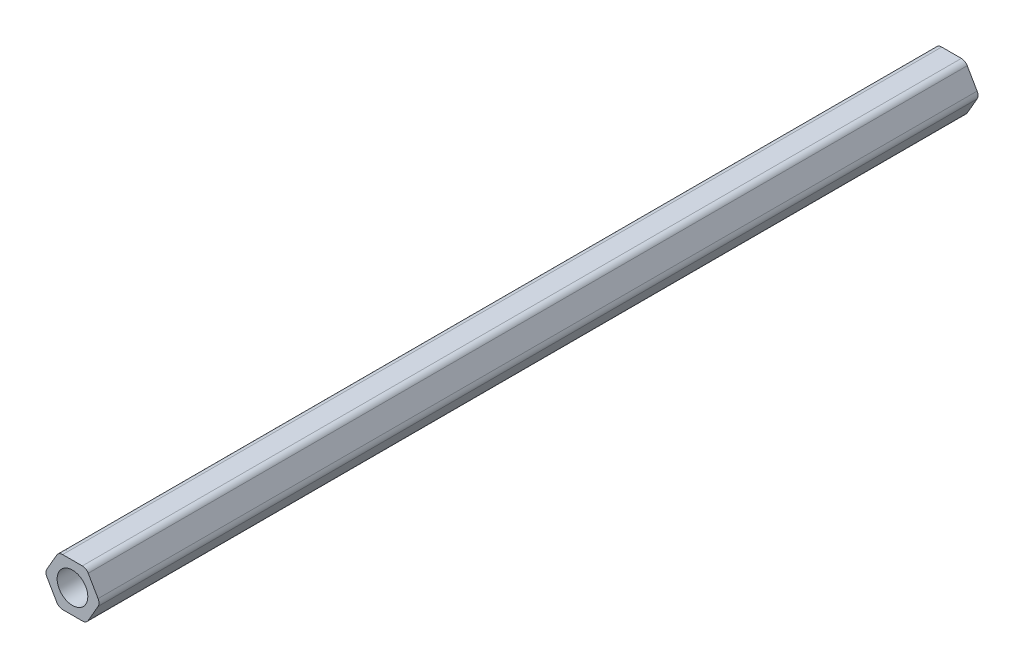
SolidWorks part; units mm, degrees
material "ABS"
ref_plane "Спереди" through (0, 0, 0) normal (0, 0, 1) x (1, 0, 0)
ref_plane "Сверху" through (0, 0, 0) normal (0, 1, 0) x (1, 0, 0)
ref_plane "Справа" through (0, 0, 0) normal (1, 0, 0) x (0, 0, -1)
sketch "Эскиз1" plane through (0, 0, 0) normal (0, 0, 1) x (1, 0, 0)
  line L1 (3.7528, 0.5) -> (2.3094, 3)
  line L2 (1.4434, 3.5) -> (-1.4434, 3.5)
  line L3 (-2.3094, 3) -> (-3.7528, 0.5)
  line L4 (-3.7528, -0.5) -> (-2.3094, -3)
  line L5 (-1.4434, -3.5) -> (1.4434, -3.5)
  line L6 (2.3094, -3) -> (3.7528, -0.5)
  circle A0 centre (0, 0) radius 3.5 construction
  circle A1 centre (0, 0) radius 2 construction
  arc A2 (-3.7528, 0.5) -> (-3.7528, -0.5) centre (-2.8868, 0) ccw
  arc A3 (-2.3094, -3) -> (-1.4434, -3.5) centre (-1.4434, -2.5) ccw
  arc A4 (1.4434, -3.5) -> (2.3094, -3) centre (1.4434, -2.5) ccw
  arc A5 (3.7528, 0.5) -> (3.7528, -0.5) centre (2.8868, 0) cw
  arc A6 (2.3094, 3) -> (1.4434, 3.5) centre (1.4434, 2.5) ccw
  arc A7 (-1.4434, 3.5) -> (-2.3094, 3) centre (-1.4434, 2.5) ccw
  dimension "D1" = 4
  dimension "D3" = 1
  dimension "D2" = 7
extrude "Бобышка-Вытянуть1" add sketch "Эскиз1" along normal blind 129
sketch "Эскиз2" plane through (0, 0, 129) normal (0, 0, 1) x (1, 0, 0)
  circle A0 centre (0, 0) radius 2.25
  dimension "D1" = 4.5
extrude "Вырез-Вытянуть1" cut sketch "Эскиз2" against normal blind 6
sketch "Эскиз3" plane through (0, 0, 0) normal (0, 0, -1) x (-1, 0, 0)
  circle A1 centre (0, 0) radius 2.25
  circle A2 centre (0, 0) radius 2.25
  dimension "D1" = 0
extrude "Вырез-Вытянуть2" cut sketch "Эскиз3" against normal blind 6
